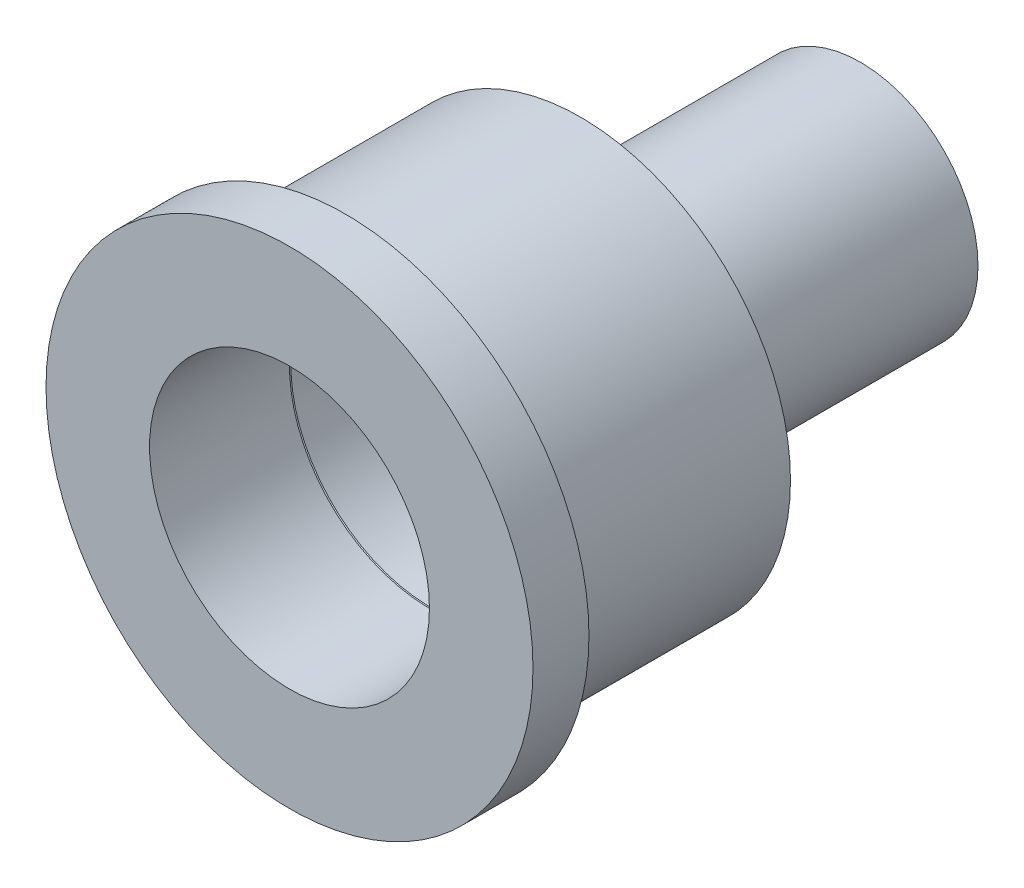
SolidWorks part; units mm, degrees
ref_plane "정면" through (0, 0, 0) normal (0, 0, 1) x (1, 0, 0)
ref_plane "윗면" through (0, 0, 0) normal (0, 1, 0) x (1, 0, 0)
ref_plane "우측면" through (0, 0, 0) normal (1, 0, 0) x (0, 0, -1)
sketch "스케치1" plane through (0, 0, 0) normal (0, 0, 1) x (1, 0, 0)
  circle A0 centre (0, 0) radius 2.1
  dimension "D1" = 4.2
extrude "보스-돌출1" add sketch "스케치1" along normal blind 5
sketch "스케치2" plane through (0, 0, 5) normal (0, 0, 1) x (1, 0, 0)
  circle A0 centre (0, 0) radius 3.75
  dimension "D1" = 7.5
extrude "보스-돌출2" add sketch "스케치2" along normal blind 4.2
sketch "스케치3" plane through (0, 0, 9.2) normal (0, 0, 1) x (1, 0, 0)
  circle A0 centre (0, 0) radius 4.35
  dimension "D1" = 8.7
extrude "보스-돌출3" add sketch "스케치3" along normal blind 1
sketch "스케치9" plane through (0, 0, 10.2) normal (0, 0, 1) x (1, 0, 0)
  circle A0 centre (0, 0) radius 2.5
  dimension "D1" = 5
extrude "컷-돌출1" cut sketch "스케치9" against normal blind 2.5
hole_wizard "M2 남비 머리 나사용 카운터보어2" positions "스케치12" profile "스케치13" counterbore size "M2" standard "ISO"
sketch "스케치12" plane through (0, 0, 7.7) normal (0, 0, 1) x (1, 0, 0)
  point P0 (0, 0)
sketch "스케치13" plane through (0, 0, 7.7) normal (1, 0, 0) x (0, -1, 0)
  line L0 (0, 0) -> (0, 8.7811)
  line L1 (0, 8.7811) -> (1.3, 8)
  line L2 (1.3, 8) -> (1.3, 1.6)
  line L3 (1.3, 1.6) -> (2.5, 1.6)
  line L5 (2.5, 1.6) -> (2.5, 0.025)
  line L6 (2.5, 0.025) -> (2.525, 0)
  line L7 (2.525, 0) -> (0, 0)
  line L8 (-2.5, 0.025) -> (-2.525, 0) construction
  line L10 (0, 8.7811) -> (-1.3, 8) construction
  line L11 (0, -6.35) -> (0, 107.95) construction
  dimension "구멍 지름" = 2.6
  dimension "구멍 깊이" = 8
  dimension "카운터보어 지름" = 5
  dimension "카운터보어 깊이" = 1.6
  dimension "표면 카운터싱크 지름" = 5.05
  dimension "표면 카운터싱크 각도" = 90
  dimension "드릴 각도" = 118
